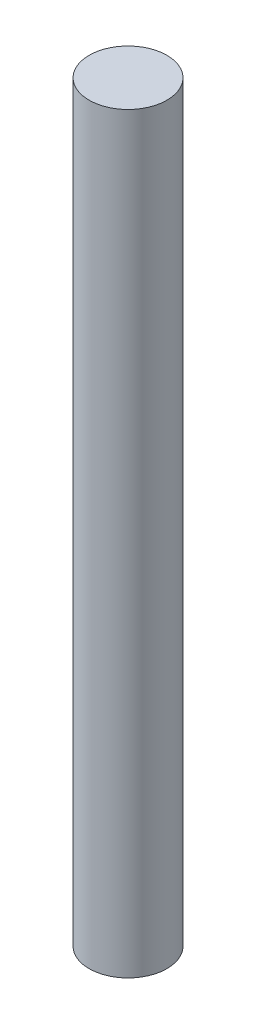
SolidWorks part; units mm, degrees
ref_plane "Front Plane" through (0, 0, 0) normal (0, 0, 1) x (1, 0, 0)
ref_plane "Top Plane" through (0, 0, 0) normal (0, 1, 0) x (1, 0, 0)
ref_plane "Right Plane" through (0, 0, 0) normal (1, 0, 0) x (0, 0, -1)
sketch "Sketch1" plane through (0, 0, 0) normal (0, 1, 0) x (1, 0, 0)
  circle A0 centre (0, 0) radius 3
  dimension "D1" = 6
extrude "Boss-Extrude1" add sketch "Sketch1" along normal blind 58
